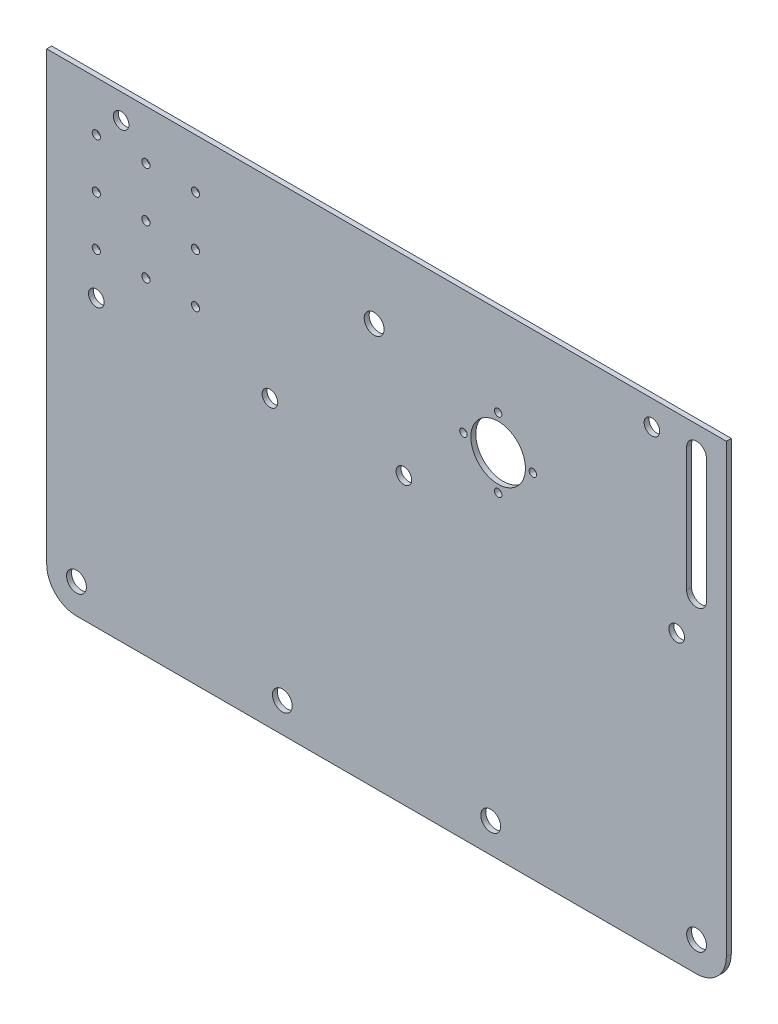
SolidWorks part; units mm, degrees
ref_plane "Front Plane" through (0, 0, 0) normal (0, 0, 1) x (1, 0, 0)
ref_plane "Top Plane" through (0, 0, 0) normal (0, 1, 0) x (1, 0, 0)
ref_plane "Right Plane" through (0, 0, 0) normal (1, 0, 0) x (0, 0, -1)
sketch "Sketch1" plane through (0, 0, 0) normal (0, 0, 1) x (1, 0, 0)
  line L0 (55, 0) -> (-55, 0) construction
  line L1 (0, 53.2731) -> (0, -38.9774) construction
  line L2 (0, -55) -> (0, 55) construction
  line L3 (-125, -12) -> (125, -12)
  line L4 (121, 120) -> (129, 120)
  line L5 (121, 120) -> (121, 170)
  line L6 (121, 170) -> (129, 170)
  line L7 (129, 120) -> (129, 170)
  line L8 (121, 120) -> (129, 170) construction
  line L9 (121, 170) -> (129, 120) construction
  line L10 (158.4448, 180) -> (-53.9982, 180)
  line L11 (137, 0) -> (137, 180)
  line L12 (137, 180) -> (158.4448, 180)
  line L13 (-53.9982, 180) -> (-137, 180)
  line L14 (-137, 180) -> (-137, 0)
  circle A0 centre (-125, 0) radius 4
  circle A1 centre (125, 0) radius 4
  circle A2 centre (125, 170) radius 4
  circle A3 centre (45, 130) radius 11
  circle A4 centre (-5, 150) radius 4
  circle A5 centre (125, 120) radius 4
  arc A6 (-125, -12) -> (-137, 0) centre (-125, 0) cw
  arc A7 (125, -12) -> (137, 0) centre (125, 0) ccw
  circle A8 centre (45, 130) radius 14 construction
  circle A9 centre (45, 144) radius 1.5
  circle A10 centre (59, 130) radius 1.5
  circle A11 centre (45, 116) radius 1.5
  circle A12 centre (31, 130) radius 1.5
  circle A13 centre (-117, 103) radius 3.15
  circle A14 centre (-47, 103) radius 3.15
  circle A15 centre (7, 103) radius 3.15
  circle A16 centre (117, 103) radius 3.15
  circle A17 centre (-107, 170) radius 3.15
  circle A18 centre (107, 170) radius 3.15
  circle A22 centre (-117, 160) radius 1.65
  circle A23 centre (-117, 140) radius 1.65
  circle A24 centre (-117, 120) radius 1.65
  circle A25 centre (-97, 160) radius 1.65
  circle A26 centre (-97, 140) radius 1.65
  circle A27 centre (-97, 120) radius 1.65
  circle A28 centre (-77, 160) radius 1.65
  circle A29 centre (-77, 140) radius 1.65
  circle A30 centre (-77, 120) radius 1.65
  circle A31 centre (-42, 0) radius 4
  circle A32 centre (42, 0) radius 4
  point P17 (125, 145)
  point P44 (45, 130)
  point P85 (0, 0)
  dimension "D2" = 8
  dimension "D4" = 22
  dimension "D11" = 12
  dimension "D13" = 12
  dimension "D14" = 28
  dimension "D15" = 3
  dimension "D17" = 6.3
  dimension "D18" = 3
  dimension "D19" = 8
  dimension "D20" = 8
  dimension "D1" = 250
  dimension "D3" = 250
  dimension "D5" = 120
  dimension "D6" = 150
  dimension "D7" = 130
  dimension "D8" = 170
  dimension "D9" = 145
  dimension "D10" = 50
  dimension "D12" = 10
  dimension "D21" = 83
  dimension "D22" = 83
  dimension "D16" = 4
extrude "Boss-Extrude1" add sketch "Sketch1" along normal blind 2 contours L3 A7 L11 L12 L10 L13 L14 A6 A0 A1 A3 A4 A5 L5 A2 L7
